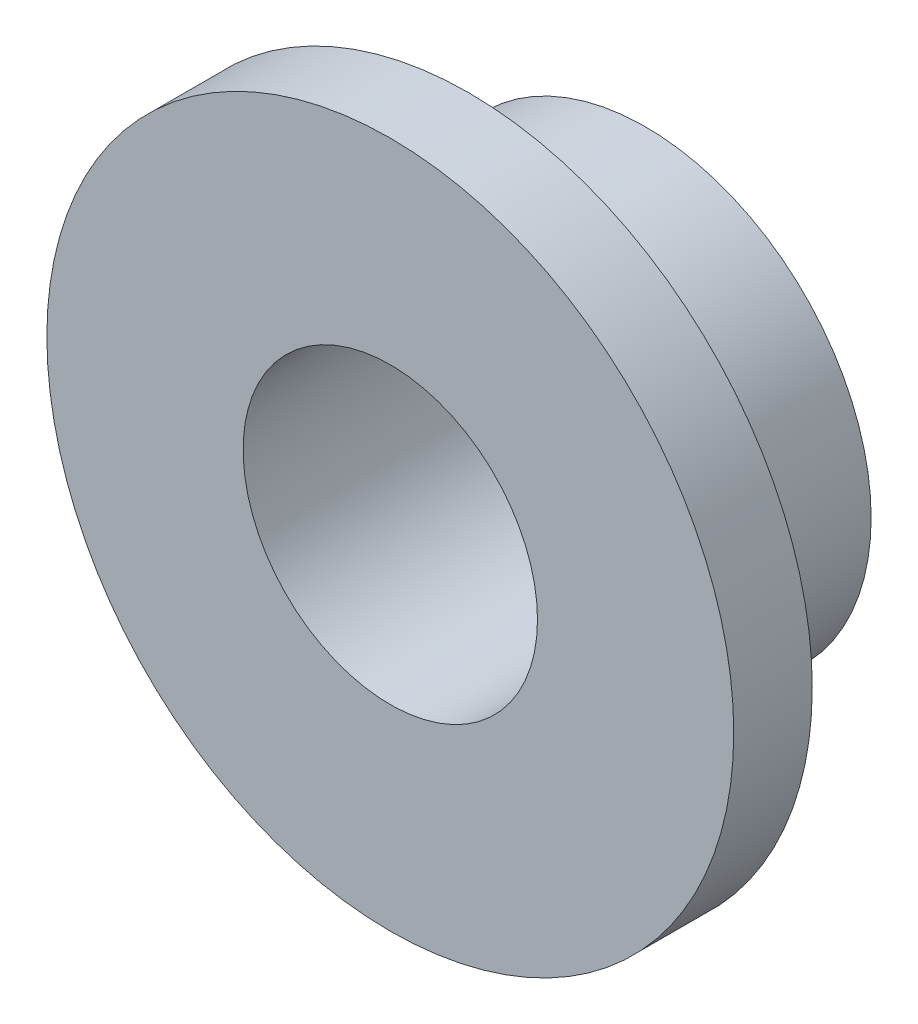
SolidWorks part; units mm, degrees
ref_plane "Alzado" through (0, 0, 0) normal (0, 0, 1) x (1, 0, 0)
ref_plane "Planta" through (0, 0, 0) normal (0, 1, 0) x (1, 0, 0)
ref_plane "Vista lateral" through (0, 0, 0) normal (1, 0, 0) x (0, 0, -1)
sketch "Croquis1" plane through (0, 0, 0) normal (0, 0, 1) x (1, 0, 0)
  circle A0 centre (0, 0) radius 7.5
  circle A1 centre (0, 0) radius 11.5
extrude "Saliente-Extruir1" add sketch "Croquis1" along normal blind 9
sketch "Croquis2" plane through (0, 0, 9) normal (0, 0, 1) x (1, 0, 0)
  circle A0 centre (0, 0) radius 7.5
  circle A1 centre (0, 0) radius 17.5
extrude "Saliente-Extruir2" add sketch "Croquis2" along normal blind 4
